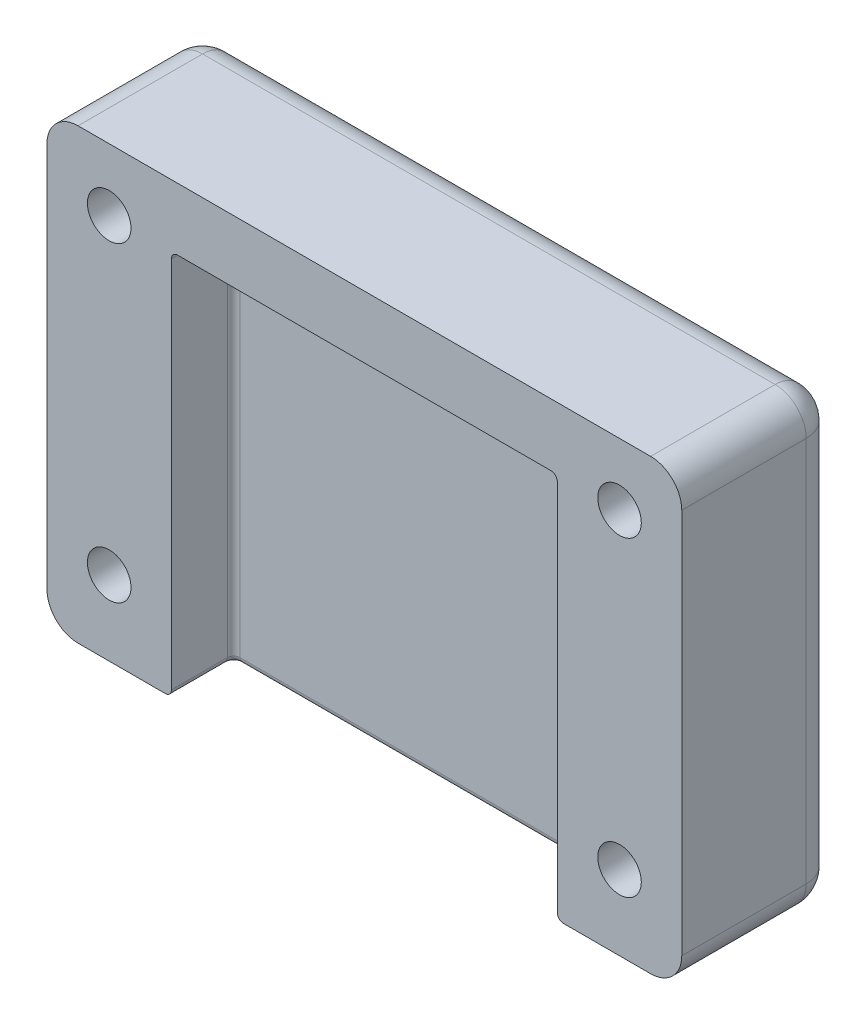
SolidWorks part; units mm, degrees
ref_plane "Front Plane" through (0, 0, 0) normal (0, 0, 1) x (1, 0, 0)
ref_plane "Top Plane" through (0, 0, 0) normal (0, 1, 0) x (1, 0, 0)
ref_plane "Right Plane" through (0, 0, 0) normal (1, 0, 0) x (0, 0, -1)
sketch "Sketch1" plane through (0, 0, 0) normal (0, 0, 1) x (1, 0, 0)
  line L0 (0, 0) -> (51, 0)
  line L1 (51, 0) -> (51, 36)
  line L2 (51, 36) -> (0, 36)
  line L3 (0, 36) -> (0, 0)
  dimension "D1" = 36
  dimension "D2" = 51
extrude "Boss-Extrude1" add sketch "Sketch1" along normal blind 12.5
sketch "Sketch2" plane through (0, 0, 12.5) normal (0, 0, 1) x (1, 0, 0)
  line L0 (10, 0) -> (10, 31)
  line L1 (0, 0) -> (51, 0) construction
  line L2 (10, 31) -> (41, 31)
  line L3 (41, 31) -> (41, 0)
  line L4 (41, 0) -> (10, 0)
  line L5 (0, 36) -> (0, 0) construction
  dimension "D1" = 31
  dimension "D2" = 31
  dimension "D3" = 10
extrude "Cut-Extrude1" cut sketch "Sketch2" against normal blind 5
sketch "Sketch3" plane through (0, 0, 12.5) normal (0, 0, 1) x (1, 0, 0)
  line L0 (0, 36) -> (0, 0) construction
  line L1 (51, 36) -> (0, 36) construction
  line L2 (51, 0) -> (51, 36) construction
  circle A0 centre (5, 31) radius 1.75
  circle A1 centre (5, 6) radius 1.75
  circle A2 centre (46, 31) radius 1.75
  circle A3 centre (46, 6) radius 1.75
  point P8 (0, 0)
  point P9 (0, 0)
  point P10 (0, 0)
  point P17 (0, 0)
  point P18 (0, 0)
  dimension "D1" = 3.5
  dimension "D2" = 3.5
  dimension "D3" = 3.5
  dimension "D4" = 3.5
  dimension "D6" = 5
  dimension "D9" = 25
  dimension "D10" = 25
  dimension "D5" = 5
  dimension "D7" = 5
  dimension "D8" = 5
extrude "Cut-Extrude2" cut sketch "Sketch3" against normal through all
fillet "Fillet1" radius 0.5 8 edges at (10, 0, 10) (25.5, 0, 7.5) (41, 0, 10) (41, 31, 10) (10, 31, 10) (10, 15.5, 7.5) (41, 15.5, 7.5) (25.5, 31, 7.5)
fillet "Fillet2" radius 2.5 8 edges at (25.5, 0, 0) (0, 18, 0) (0, 36, 6.25) (51, 36, 6.25) (25.5, 36, 0) (51, 18, 0) (51, 0, 6.25) (0, 0, 6.25)
